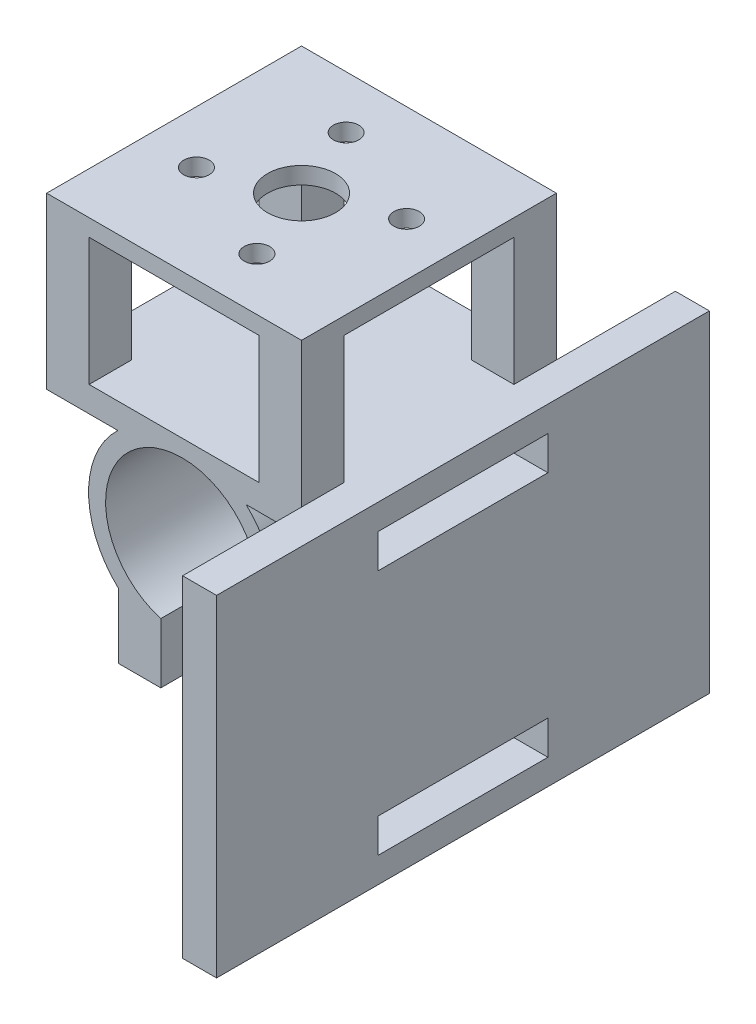
SolidWorks part; units mm, degrees
material "ABS generico"
ref_plane "Piano frontale" through (0, 0, 0) normal (0, 0, 1) x (1, 0, 0)
ref_plane "Piano superiore" through (0, 0, 0) normal (0, 1, 0) x (1, 0, 0)
ref_plane "Piano destro" through (0, 0, 0) normal (1, 0, 0) x (0, 0, -1)
sketch "Schizzo1" plane through (0, 0, 0) normal (0, 0, 1) x (1, 0, 0)
  line L0 (-2.5, -10.7121) -> (-2.5, -15.7121)
  line L2 (-2.5, -8.6458) -> (-2.5, -10.7121)
  line L4 (2.5, -8.6458) -> (2.5, -10.7121)
  line L5 (-2.5, -15.7121) -> (-7.5, -15.7121)
  line L6 (-7.5, -15.7121) -> (-7.5, -8.0467)
  line L7 (2.5, -10.7121) -> (2.5, -15.7121)
  line L8 (2.5, -15.7121) -> (7.5, -15.7121)
  line L9 (7.5, -15.7121) -> (7.5, -8.0467)
  line L10 (7.5498, 8) -> (14.0646, 8)
  line L11 (-15.9354, 11) -> (14.0646, 11)
  line L12 (-15.9354, 11) -> (-15.9354, 8)
  line L13 (-15.9354, 8) -> (-7.5498, 8)
  line L14 (14.0646, 11) -> (14.0646, 8)
  arc A0 (2.5, -8.6458) -> (-2.5, -8.6458) centre (0, 0) ccw
  arc A1 (7.5, -8.0467) -> (7.5498, 8) centre (0, 0) ccw
  arc A2 (-7.5498, 8) -> (-7.5, -8.0467) centre (0, 0) ccw
  dimension "D1" = 18
  dimension "D2" = 22
  dimension "D3" = 5
  dimension "D4" = 2.0663
  dimension "D5" = 5
  dimension "D6" = 5
  dimension "D7" = 7.6654
  dimension "D8" = 5
  dimension "D9" = 30
  dimension "D10" = 3
  dimension "D11" = 6.5147
extrude "SupportoMotore" add sketch "Schizzo1" along normal blind 30
sketch "Schizzo2" plane through (14.0646, 0, 0) normal (1, 0, 0) x (0, 0, -1)
  line L1 (14, 11) -> (-44, 11)
  line L2 (14, 11) -> (14, -28)
  line L3 (14, -28) -> (-44, -28)
  line L4 (-44, 11) -> (-44, -28)
  line L7 (-30, 11) -> (0, 11) construction
  line L8 (-15, -15.7121) -> (-15, -28) construction
  line L9 (-30, -15.7121) -> (0, -15.7121) construction
  dimension "D1" = 39
  dimension "D2" = 58
extrude "SupportoESC" add sketch "Schizzo2" along normal blind 4
sketch "Schizzo3" plane through (14.0646, 0, 0) normal (-1, 0, 0) x (0, 0, 1)
  line L0 (-14, 8) -> (-14, -28) construction
  line L1 (-14, -28) -> (-14, 11) construction
  line L2 (-14, -10) -> (44, -10) construction
  line L3 (44, 11) -> (44, -28) construction
  line L4 (22, -6) -> (22, -14) construction
  line L5 (8, -6) -> (8, -14) construction
  line L6 (30, -15.7121) -> (22, -14) construction
  line L7 (8, -14) -> (0, -15.7121) construction
  circle A0 centre (22, -14) radius 3 construction
  circle A1 centre (8, -14) radius 3 construction
  circle A2 centre (22, -6) radius 3
  circle A3 centre (8, -6) radius 3
  point P8 (22, -10)
  dimension "D1" = 6
  dimension "D2" = 8
  dimension "D3" = 8
extrude "ColonneSupportoESC" add sketch "Schizzo3" along normal up to body separate body
sketch "Schizzo7" plane through (0, 11, 0) normal (0, 1, 0) x (1, 0, 0)
  line L1 (-15.9354, -30) -> (-10.9354, -30)
  line L2 (-15.9354, -30) -> (-15.9354, -25)
  line L3 (-15.9354, -25) -> (-10.9354, -25)
  line L4 (-10.9354, -30) -> (-10.9354, -25)
  line L5 (9.0646, -30) -> (9.0646, -25)
  line L6 (9.0646, -30) -> (14.0646, -30)
  line L7 (14.0646, -30) -> (14.0646, -25)
  line L8 (9.0646, -25) -> (14.0646, -25)
  line L9 (9.0646, -5) -> (9.0646, 0)
  line L10 (9.0646, -5) -> (14.0646, -5)
  line L11 (14.0646, -5) -> (14.0646, 0)
  line L12 (9.0646, 0) -> (14.0646, 0)
  line L13 (-15.9354, -5) -> (-15.9354, 0)
  line L14 (-15.9354, -5) -> (-10.9354, -5)
  line L15 (-10.9354, -5) -> (-10.9354, 0)
  line L16 (-15.9354, 0) -> (-10.9354, 0)
  line L17 (14.0646, 0) -> (-15.9354, 0) construction
  line L18 (14.0646, 14) -> (14.0646, 0) construction
  line L19 (-15.9354, -30) -> (-15.9354, 0) construction
  dimension "D1" = 5
  dimension "D2" = 2
  dimension "D3" = 2
extrude "SupportiBaseMotore" add sketch "Schizzo7" along normal blind 15
sketch "Schizzo8" plane through (0, 26, 0) normal (0, 1, 0) x (1, 0, 0)
  line L1 (14.0646, -30) -> (-15.9354, -30)
  line L2 (14.0646, -30) -> (14.0646, 0)
  line L3 (14.0646, 0) -> (-15.9354, 0)
  line L4 (-15.9354, -30) -> (-15.9354, 0)
extrude "BaseMotore" add sketch "Schizzo8" along normal blind 2
sketch "Schizzo9" plane through (0, 28, 0) normal (0, 1, 0) x (1, 0, 0)
  line L0 (-15.9354, 0) -> (-15.9354, -30) construction
  line L1 (14.0646, 0) -> (-15.9354, 0) construction
  line L2 (2.6233, -23.8082) -> (-0.9354, -15) construction
  line L3 (-0.9354, -15) -> (-0.9354, -30) construction
  line L4 (-15.9354, -30) -> (14.0646, -30) construction
  circle A0 centre (-0.9354, -15) radius 9.5 construction
  circle A1 centre (2.6233, -23.8082) radius 1.5
  circle A2 centre (-9.7437, -18.5588) radius 1.5
  circle A3 centre (-4.4942, -6.1918) radius 1.5
  circle A4 centre (7.8728, -11.4412) radius 1.5
  circle A5 centre (-0.9354, -15) radius 4
  point P4 (-15.9354, -15)
  point P7 (-0.9354, 0)
  point P22 (-0.9354, -15)
  dimension "D1" = 19
  dimension "D2" = 3
  dimension "D5" = 8
  dimension "D3" = 22
  dimension "D4" = 4
extrude "ForiAggancioMotore" cut sketch "Schizzo9" against normal up to surface (2 mm away) up to face at (-0.9354, 26, 15)
sketch "Schizzo10" plane through (18.0646, 0, 0) normal (1, 0, 0) x (0, 0, -1)
  line L0 (-25, 26) -> (-25, 11) construction
  line L1 (-25, 8) -> (-5, 8)
  line L2 (-25, 8) -> (-25, 4)
  line L3 (-25, 4) -> (-5, 4)
  line L4 (-5, 8) -> (-5, 4)
  line L5 (-5, 26) -> (-5, 11) construction
  line L6 (14, 11) -> (-44, 11) construction
  line L7 (-44, -8.5) -> (14, -8.5) construction
  line L8 (-44, 11) -> (-44, -28) construction
  line L9 (14, -28) -> (14, 11) construction
  line L10 (-25, -21) -> (-5, -21)
  line L11 (-5, -25) -> (-5, -21)
  line L12 (-25, -25) -> (-5, -25)
  line L13 (-25, -25) -> (-25, -21)
  dimension "D1" = 4
  dimension "D2" = 3
extrude "AperturaFascetta" cut sketch "Schizzo10" against normal up to surface (4 mm away) up to face at (14.0646, -6, 11)
ref_plane "PianoSimmetriaBaseESC" through (0, -8.5, 0) normal (0, 1, 0) x (1, 0, 0)
ref_plane "PianoSimmetriaCastelloMotore" through (0, 0, 15) normal (0, 0, 1) x (1, 0, 0)
ref_plane "PianoSimmetriaForiSuperiori" through (-0.9354, 0, 0) normal (1, 0, 0) x (0, 0, -1)
